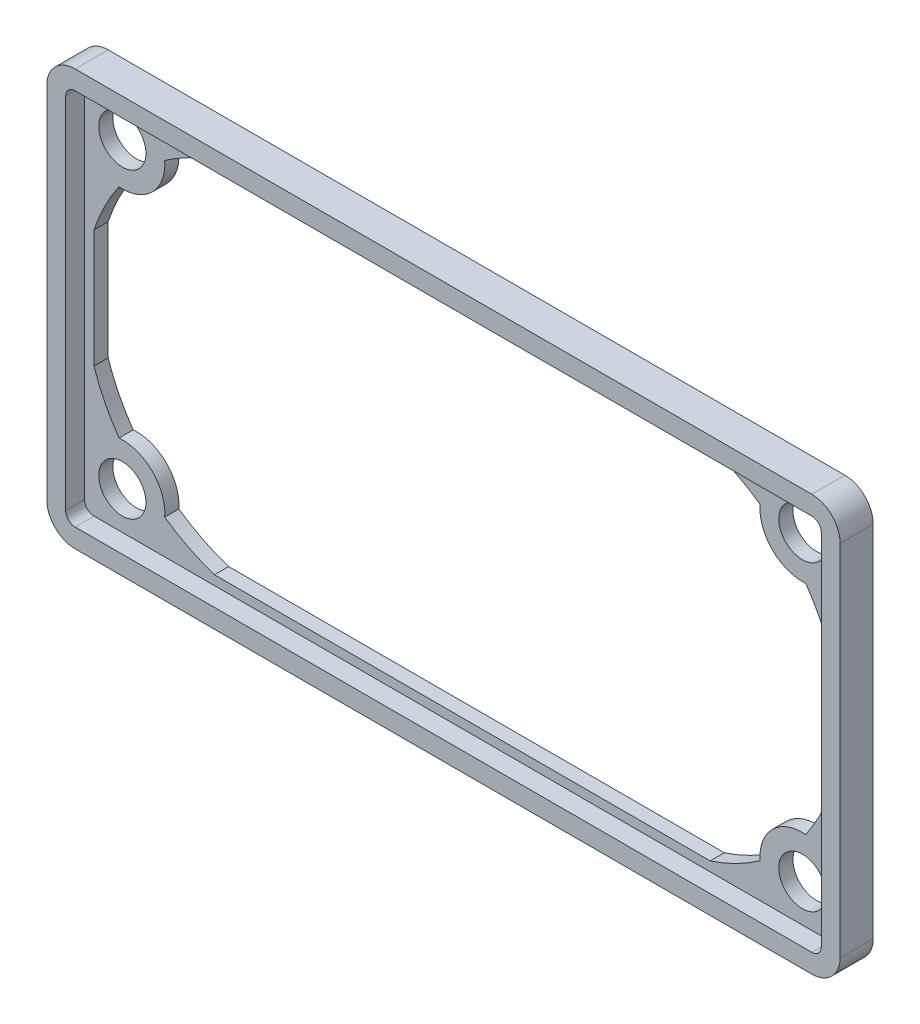
SolidWorks part; units mm, degrees
ref_plane "Front Plane" through (0, 0, 0) normal (0, 0, 1) x (1, 0, 0)
ref_plane "Top Plane" through (0, 0, 0) normal (0, 1, 0) x (1, 0, 0)
ref_plane "Right Plane" through (0, 0, 0) normal (1, 0, 0) x (0, 0, -1)
sketch "Sketch1" plane through (0, 0, 0) normal (0, 0, 1) x (1, 0, 0)
  line L0 (0, 20) -> (-40, -20) construction
  line L1 (39, 20) -> (-39, 20)
  line L2 (0, 20) -> (0, -20) construction
  line L3 (39, -20) -> (-39, -20)
  line L4 (-40, 19) -> (-40, -19)
  line L5 (40, 19) -> (40, -19)
  line L6 (26.245, 19) -> (-26.245, 19)
  line L7 (-39, 6.245) -> (-39, -6.245)
  line L8 (26.245, -19) -> (-26.245, -19)
  line L9 (39, 6.245) -> (39, -6.245)
  line L10 (-1, 6.245) -> (-1, -6.245) construction
  line L11 (1, 6.245) -> (1, -6.245) construction
  line L12 (-13.755, 19) -> (-26.245, 19) construction
  line L13 (1, 20) -> (1, -20) construction
  line L14 (-1, 20) -> (-1, -20) construction
  line L15 (-13.755, -19) -> (-26.245, -19) construction
  line L16 (39, 19) -> (-39, 19) construction
  line L17 (-39, 19) -> (-39, -19) construction
  line L18 (39, -19) -> (-39, -19) construction
  line L19 (40, 20) -> (-40, 20) construction
  line L20 (39, 19) -> (39, -19) construction
  line L21 (-40, 20) -> (-40, -20) construction
  line L22 (40, -20) -> (-40, -20) construction
  line L23 (40, 20) -> (40, -20) construction
  line L24 (39, 0) -> (-39, 0) construction
  arc A0 (-26.245, 19) -> (-31.5139, 16.3533) centre (-20, 0) ccw
  circle A1 centre (-36, 16) radius 2.5
  circle A2 centre (-4, 16) radius 2.5 construction
  circle A3 centre (-4, -16) radius 2.5 construction
  circle A4 centre (-36, -16) radius 2.5
  circle A5 centre (36, -16) radius 2.5
  circle A6 centre (4, -16) radius 2.5 construction
  circle A7 centre (4, 16) radius 2.5 construction
  circle A8 centre (36, 16) radius 2.5
  arc A9 (1, 6.245) -> (13.755, 19) centre (20, 0) cw construction
  arc A10 (-39, -6.245) -> (-36.3533, -11.5139) centre (-20, 0) ccw
  arc A11 (-13.755, -19) -> (-1, -6.245) centre (-20, 0) ccw construction
  arc A12 (-1, 6.245) -> (-13.755, 19) centre (-20, 0) ccw construction
  arc A13 (13.755, -19) -> (1, -6.245) centre (20, 0) cw construction
  arc A14 (39, -6.245) -> (36.3533, -11.5139) centre (20, 0) cw
  arc A15 (26.245, 19) -> (31.5139, 16.3533) centre (20, 0) cw
  arc A16 (-39, 20) -> (-40, 19) centre (-39, 19) ccw
  arc A17 (-39, -20) -> (-40, -19) centre (-39, -19) cw
  arc A18 (40, -19) -> (39, -20) centre (39, -19) cw
  arc A19 (40, 19) -> (39, 20) centre (39, 19) ccw
  arc A20 (36.3533, 11.5139) -> (31.5139, 16.3533) centre (36, 16) cw
  arc A21 (36.3533, 11.5139) -> (39, 6.245) centre (20, 0) cw
  circle A22 centre (36, 16) radius 4.5 construction
  arc A23 (-36.3533, 11.5139) -> (-31.5139, 16.3533) centre (-36, 16) ccw
  arc A24 (-36.3533, -11.5139) -> (-31.5139, -16.3533) centre (-36, -16) cw
  arc A25 (36.3533, -11.5139) -> (31.5139, -16.3533) centre (36, -16) ccw
  arc A26 (-36.3533, 11.5139) -> (-39, 6.245) centre (-20, 0) ccw
  arc A27 (-31.5139, -16.3533) -> (-26.245, -19) centre (-20, 0) ccw
  arc A28 (31.5139, -16.3533) -> (26.245, -19) centre (20, 0) cw
  point P6 (0, 0)
  point P9 (-20, 0)
  point P19 (-20, 0)
  point P55 (-40, 20)
  point P69 (40.5, 16)
  point P77 (0, 0)
  dimension "D1" = 1
  dimension "D3" = 5
  dimension "D9" = 1
  dimension "D2" = 40
  dimension "D5" = 32
  dimension "D6" = 40
  dimension "D7" = 1
  dimension "D8" = 1
  dimension "D10" = 2
  dimension "D4" = 4
extrude "Boss-Extrude1" add sketch "Sketch1" along normal blind 1.5
sketch "Sketch2" plane through (0, 0, 0) normal (0, 0, -1) x (-1, 0, 0)
  line L0 (39, 22) -> (-39, 22)
  line L1 (-42, 19) -> (-42, -19)
  line L2 (-39, -22) -> (39, -22)
  line L3 (42, -19) -> (42, 19)
  line L4 (40, -19) -> (40, 19)
  line L5 (-39, -20) -> (39, -20)
  line L6 (-40, 19) -> (-40, -19)
  line L7 (39, 20) -> (-39, 20)
  line L8 (40, -19) -> (40, 19)
  line L9 (-39, -20) -> (39, -20)
  line L10 (-40, 19) -> (-40, -19)
  line L11 (39, 20) -> (-39, 20)
  arc A0 (42, 19) -> (39, 22) centre (39, 19) ccw
  arc A1 (-39, 22) -> (-42, 19) centre (-39, 19) ccw
  arc A2 (-42, -19) -> (-39, -22) centre (-39, -19) ccw
  arc A3 (39, -22) -> (42, -19) centre (39, -19) ccw
  arc A4 (40, 19) -> (39, 20) centre (39, 19) ccw
  arc A5 (39, -20) -> (40, -19) centre (39, -19) ccw
  arc A6 (-40, -19) -> (-39, -20) centre (-39, -19) ccw
  arc A7 (-39, 20) -> (-40, 19) centre (-39, 19) ccw
  arc A8 (40, 19) -> (39, 20) centre (39, 19) ccw
  arc A9 (39, -20) -> (40, -19) centre (39, -19) ccw
  arc A10 (-40, -19) -> (-39, -20) centre (-39, -19) ccw
  arc A11 (-39, 20) -> (-40, 19) centre (-39, 19) ccw
  dimension "D1" = 0
  dimension "D2" = 2
extrude "Boss-Extrude2" add sketch "Sketch2" against normal blind 3.5
